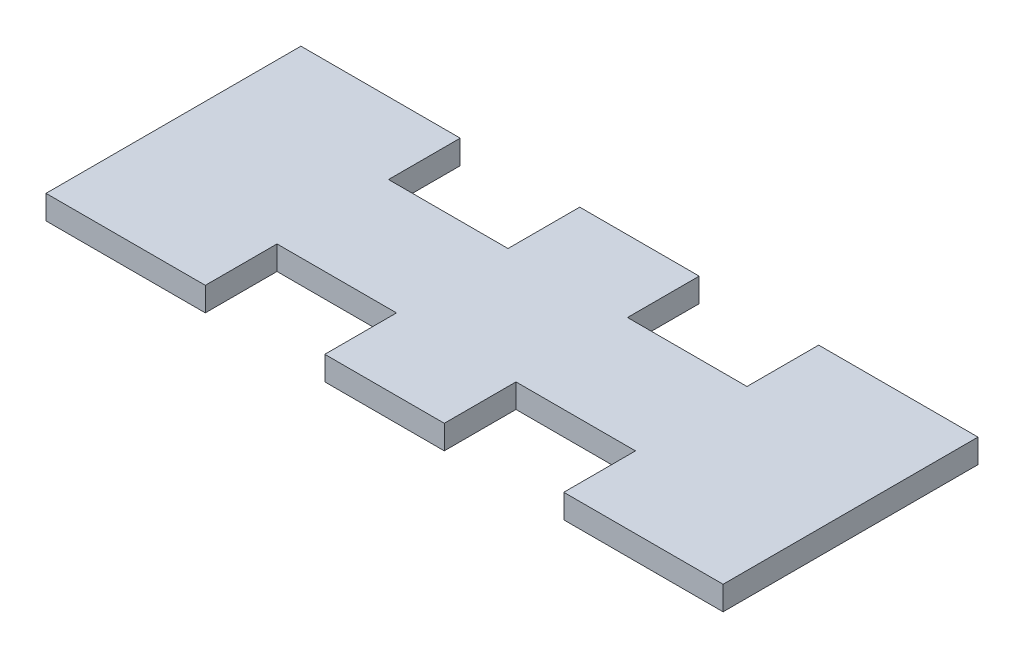
SolidWorks part; units mm, degrees
ref_plane "Alzado" through (0, 0, 0) normal (0, 0, 1) x (1, 0, 0)
ref_plane "Planta" through (0, 0, 0) normal (0, 1, 0) x (1, 0, 0)
ref_plane "Vista lateral" through (0, 0, 0) normal (1, 0, 0) x (0, 0, -1)
sketch "Croquis1" plane through (0, 0, 0) normal (0, 1, 0) x (1, 0, 0)
  line L0 (0, 0) -> (20, 0)
  line L1 (20, 0) -> (20, 9)
  line L2 (20, 9) -> (35, 9)
  line L3 (35, 9) -> (35, 0)
  line L4 (35, 0) -> (50, 0)
  line L6 (85, 0) -> (65, 0)
  line L7 (50, 9) -> (50, 0)
  line L8 (65, 9) -> (50, 9)
  line L9 (65, 0) -> (65, 9)
  line L10 (0, 0) -> (0, 32)
  line L11 (0, 32) -> (20, 32)
  line L12 (20, 32) -> (20, 23)
  line L13 (20, 23) -> (35, 23)
  line L14 (35, 23) -> (35, 32)
  line L15 (35, 32) -> (50, 32)
  line L16 (50, 32) -> (50, 23)
  line L17 (50, 23) -> (65, 23)
  line L18 (65, 23) -> (65, 32)
  line L19 (65, 32) -> (85, 32)
  line L20 (85, 32) -> (85, 0)
  dimension "D1" = 20
  dimension "D2" = 9
  dimension "D3" = 15
  dimension "D4" = 15
  dimension "D5" = 32
  dimension "D6" = 9
  dimension "D7" = 9
  dimension "D8" = 9
  dimension "D9" = 9
  dimension "D10" = 9
  dimension "D11" = 9
extrude "Saliente-Extruir1" add sketch "Croquis1" along normal blind 3
